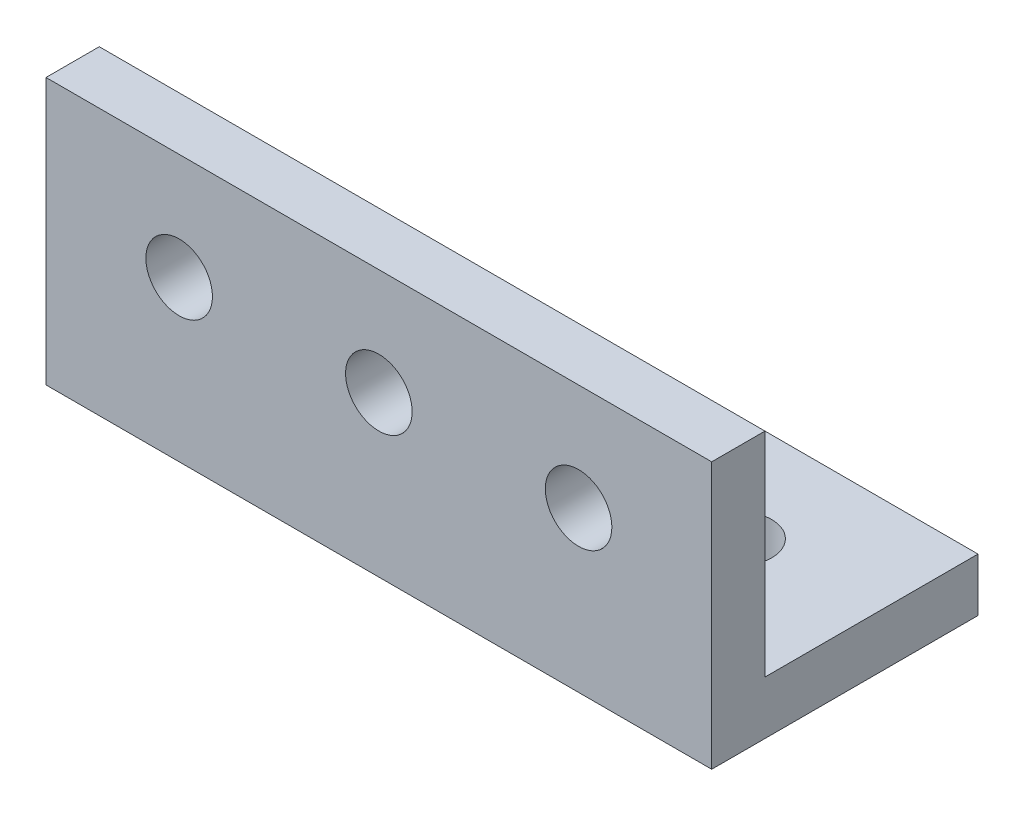
SolidWorks part; units mm, degrees
ref_plane "Спереди" through (0, 0, 0) normal (0, 0, 1) x (1, 0, 0)
ref_plane "Сверху" through (0, 0, 0) normal (0, 1, 0) x (1, 0, 0)
ref_plane "Справа" through (0, 0, 0) normal (1, 0, 0) x (0, 0, -1)
sketch "Эскиз1" plane through (0, 0, 0) normal (0, 1, 0) x (1, 0, 0)
  line L0 (0, 12) -> (50, 12) construction
  line L1 (0, 0) -> (50, 0)
  line L2 (0, 0) -> (0, 20)
  line L3 (0, 20) -> (50, 20)
  line L4 (50, 0) -> (50, 20)
  circle A0 centre (10, 12) radius 2.5
  circle A1 centre (40, 12) radius 2.5
  circle A2 centre (25, 12) radius 2.5
  dimension "D4" = 5
  dimension "D5" = 5
  dimension "D8" = 5
  dimension "D1" = 50
  dimension "D2" = 20
  dimension "D3" = 12
  dimension "D6" = 10
  dimension "D7" = 30
  dimension "D9" = 15
extrude "Бобышка-Вытянуть1" add sketch "Эскиз1" along normal blind 4
sketch "Эскиз2" plane through (0, 4, 0) normal (0, 1, 0) x (1, 0, 0)
  line L0 (50, 0) -> (50, 20) construction
  line L1 (0, 0) -> (50, 0)
  line L2 (0, 0) -> (0, 4)
  line L3 (0, 4) -> (50, 4)
  line L4 (50, 0) -> (50, 4)
  dimension "D1" = 4
extrude "Бобышка-Вытянуть2" add sketch "Эскиз2" along normal blind 16
sketch "Эскиз3" plane through (0, 0, 0) normal (0, 0, 1) x (1, 0, 0)
  line L0 (0, 12) -> (50, 12) construction
  line L1 (0, 20) -> (0, 0) construction
  line L2 (50, 20) -> (50, 0) construction
  line L3 (0, 0) -> (50, 0) construction
  circle A0 centre (10, 12) radius 2.5
  circle A1 centre (40, 12) radius 2.5
  circle A2 centre (25, 12) radius 2.5
  dimension "D2" = 5
  dimension "D3" = 5
  dimension "D6" = 5
  dimension "D1" = 12
  dimension "D4" = 10
  dimension "D5" = 30
  dimension "D7" = 15
extrude "Вырез-Вытянуть1" cut sketch "Эскиз3" against normal blind 4
